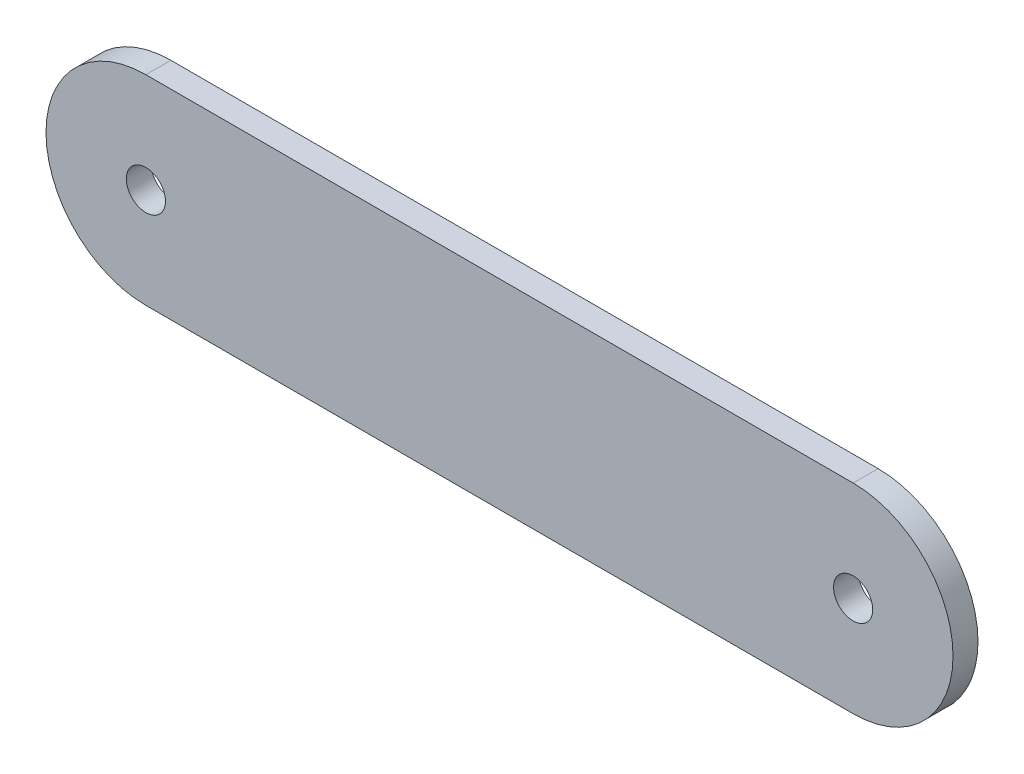
SolidWorks part; units mm, degrees
ref_plane "Front Plane" through (0, 0, 0) normal (1, 0, 0) x (0, 1, 0)
ref_plane "Top Plane" through (0, 0, 0) normal (0, 0, 1) x (0, 1, 0)
ref_plane "Right Plane" through (0, 0, 0) normal (0, 1, 0) x (-1, 0, 0)
sketch "Sketch1" plane through (0, 0, 0) normal (0, 0, 1) x (0, 1, 0)
  line L2 (-12.7, -49.1513) -> (-12.7, 40.7647)
  line L4 (12.7, -49.1513) -> (12.7, 40.7647)
  line L5 (-12.5385, -51.1701) -> (11.3735, 46.4156) construction
  line L6 (-11.3735, 46.4156) -> (12.5385, -51.1701) construction
  arc A0 (12.7, 40.7647) -> (-12.7, 40.7647) centre (0, 40.7647) ccw
  arc A1 (-12.7, -49.1513) -> (12.7, -49.1513) centre (0, -49.1513) ccw
  point P0 (0, 0)
  point P2 (0, 40.7647)
  point P13 (0, 40.7647)
  point P14 (0, -49.1513)
  dimension "D1" = 89.916
extrude "Boss-Extrude1" add sketch "Sketch1" along normal blind 3.175
sketch "Sketch2" plane through (0, 0, 3.175) normal (0, 0, 1) x (1, 0, 0)
  point P0 (-40.7647, 0)
  point P1 (49.1513, 0)
  point P6 (0, 0)
  point P7 (0, 0)
hole_wizard "#9 (0.196) Diameter Hole1" positions "Sketch2" profile "Sketch3" hole size "#9" standard "ANSI Inch" end condition through all
sketch "Sketch3" plane through (-40.7647, 0, 3.175) normal (1, 0, 0) x (0, -1, 0)
  line L0 (0, 0) -> (0, 3.175)
  line L1 (0, 3.175) -> (2.4892, 3.175)
  line L2 (2.4892, 3.175) -> (2.4892, 0)
  line L5 (2.4892, 0) -> (0, 0)
  line L11 (0, -6.35) -> (0, 107.95) construction
  dimension "Thru Hole Dia." = 4.9784
  dimension "Thru Hole Depth" = 3.175
